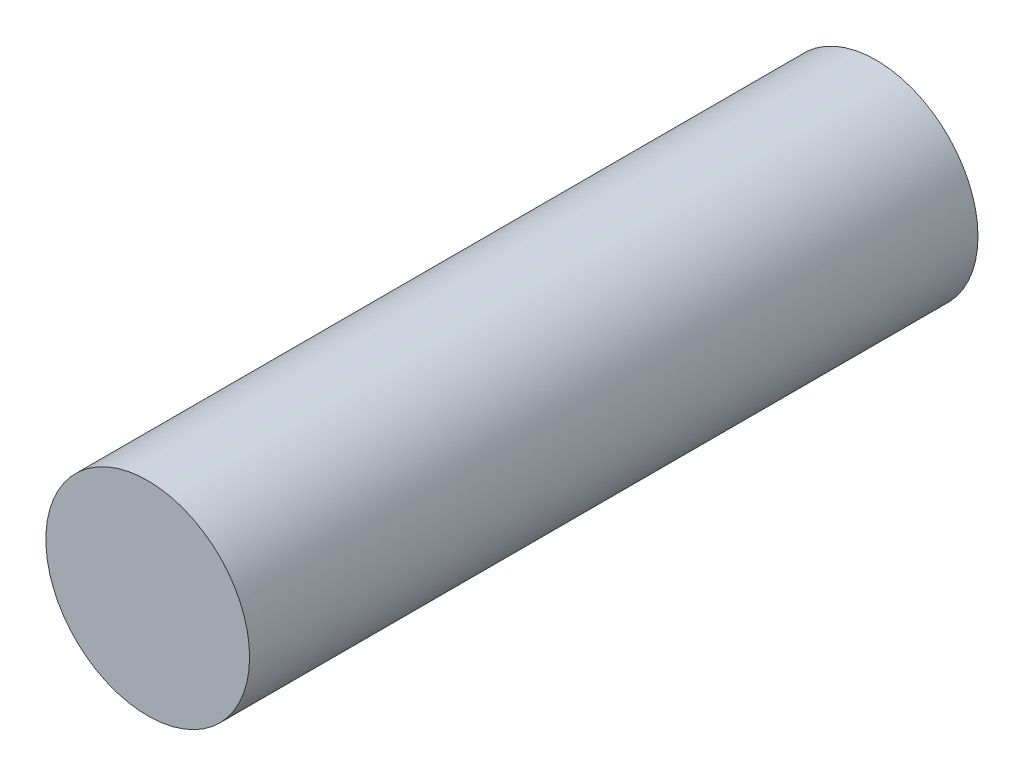
SolidWorks part; units mm, degrees
ref_plane "前视基准面" through (0, 0, 0) normal (0, 0, 1) x (1, 0, 0)
ref_plane "上视基准面" through (0, 0, 0) normal (0, 1, 0) x (1, 0, 0)
ref_plane "右视基准面" through (0, 0, 0) normal (1, 0, 0) x (0, 0, -1)
other "Configuration Table"
sketch "草图1" plane through (0, 0, 0) normal (0, 0, 1) x (1, 0, 0)
  circle A0 centre (0, 0) radius 2
extrude "凸台-拉伸1" add sketch "草图1" along normal blind 14.3
